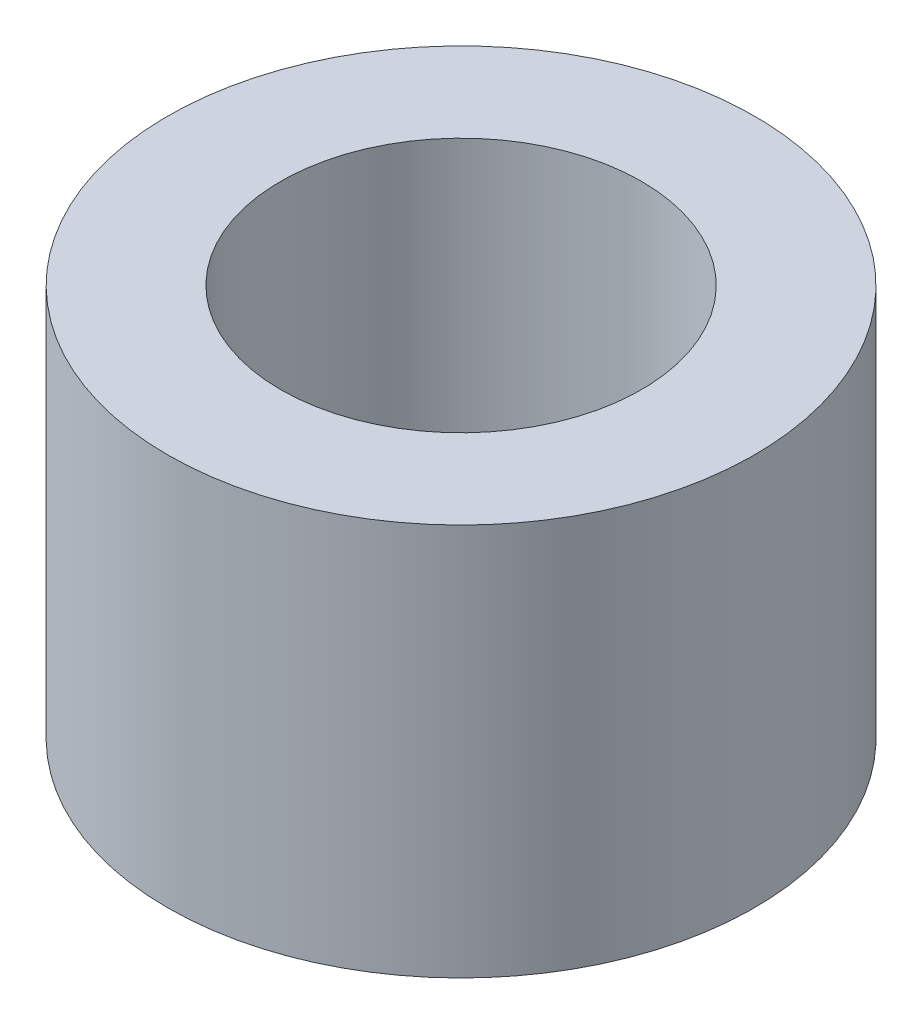
SolidWorks part; units mm, degrees
ref_plane "Front Plane" through (0, 0, 0) normal (0, 0, 1) x (1, 0, 0)
ref_plane "Top Plane" through (0, 0, 0) normal (0, 1, 0) x (1, 0, 0)
ref_plane "Right Plane" through (0, 0, 0) normal (1, 0, 0) x (0, 0, -1)
sketch "Sketch1" plane through (0, 0, 0) normal (0, 1, 0) x (1, 0, 0)
  circle A0 centre (0, 0) radius 1.4605
  circle A1 centre (0, 0) radius 2.3749
  dimension "D1" = 2.921
  dimension "D2" = 4.7498
extrude "Boss-Extrude1" add sketch "Sketch1" along normal blind 3.175
